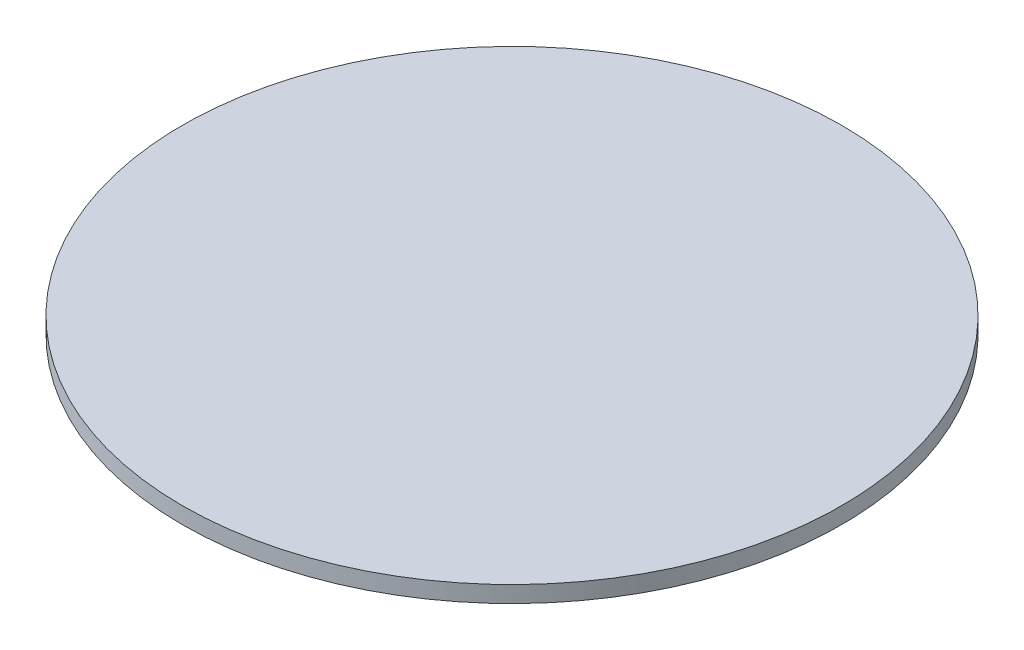
SolidWorks part; units mm, degrees
ref_plane "Front Plane" through (0, 0, 0) normal (0, 0, 1) x (1, 0, 0)
ref_plane "Top Plane" through (0, 0, 0) normal (0, 1, 0) x (1, 0, 0)
ref_plane "Right Plane" through (0, 0, 0) normal (1, 0, 0) x (0, 0, -1)
sketch "Sketch1" plane through (0, 0, 0) normal (0, 1, 0) x (1, 0, 0)
  circle A0 centre (0, 0) radius 100
  dimension "D1" = 200
extrude "Boss-Extrude1" add sketch "Sketch1" along normal blind 5
sketch "Sketch2" plane through (0, 0, 0) normal (0, -1, 0) x (1, 0, 0)
  circle A0 centre (0, 0) radius 91.5 construction
  circle A1 centre (0, 0) radius 94
  circle A2 centre (0, 0) radius 89
  dimension "D1" = 183
  dimension "D2" = 2.5
  dimension "D3" = 5
